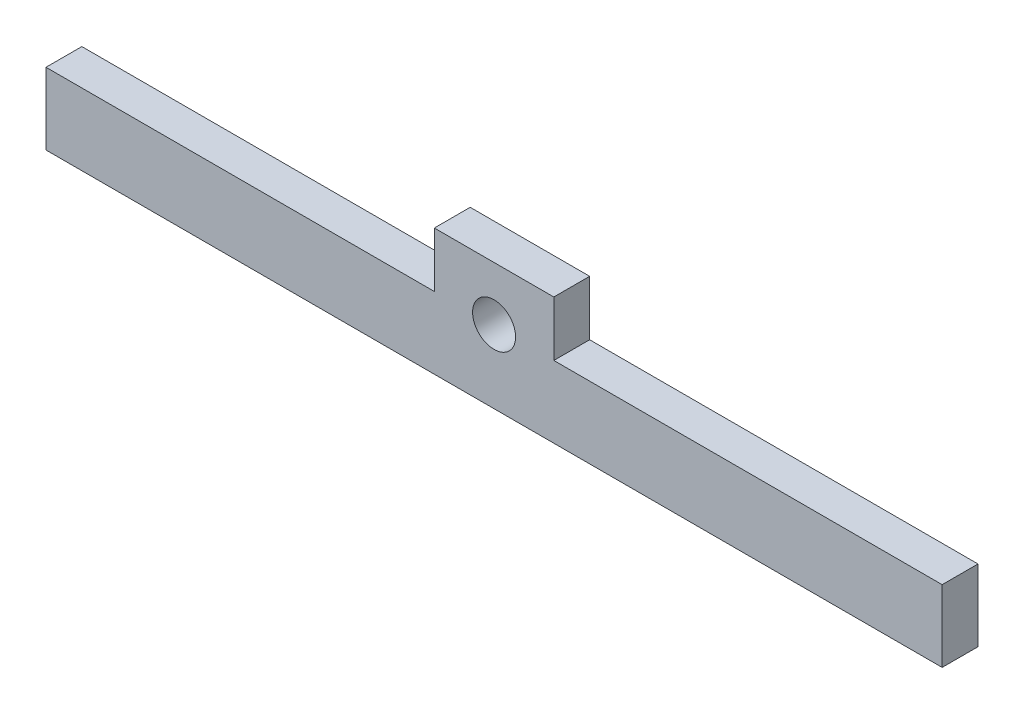
SolidWorks part; units mm, degrees
ref_plane "Alzado" through (0, 0, 0) normal (0, 0, 1) x (1, 0, 0)
ref_plane "Planta" through (0, 0, 0) normal (0, 1, 0) x (1, 0, 0)
ref_plane "Vista lateral" through (0, 0, 0) normal (1, 0, 0) x (0, 0, -1)
sketch "Croquis1" plane through (0, 0, 0) normal (0, 0, 1) x (1, 0, 0)
  line L0 (-187.5, 0) -> (187.5, 0)
  line L2 (-25, 30) -> (-25, 53)
  line L3 (-25, 53) -> (25, 53)
  line L4 (25, 30) -> (25, 53)
  line L9 (-25, 30) -> (-187.5, 30)
  line L10 (-187.5, 0) -> (-187.5, 30)
  line L13 (25, 30) -> (187.5, 30)
  line L14 (187.5, 0) -> (187.5, 30)
  circle A0 centre (0, 30.5) radius 9
  point P0 (0, 0)
  dimension "D3" = 18
  dimension "D1" = 375
  dimension "D2" = 50
  dimension "D4" = 30.5
  dimension "D5" = 30
  dimension "D6" = 25
  dimension "D7" = 53
extrude "Saliente-Extruir1" add sketch "Croquis1" along normal blind 15
